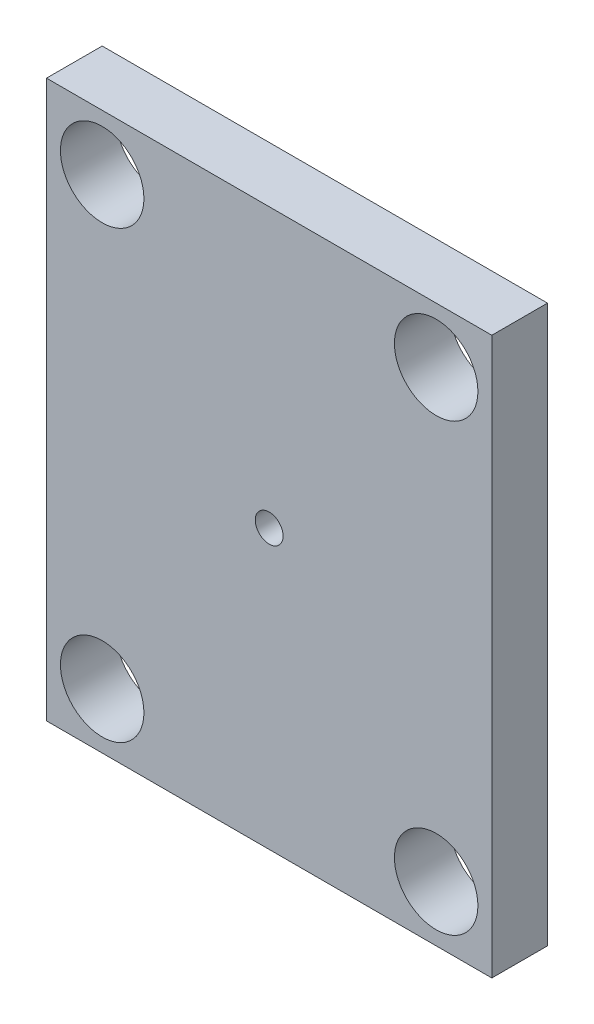
SolidWorks part; units mm, degrees
material "6061 Alloy"
ref_plane "Front" through (0, 0, 0) normal (0, 0, 1) x (1, 0, 0)
ref_plane "Top" through (0, 0, 0) normal (0, 1, 0) x (1, 0, 0)
ref_plane "Right" through (0, 0, 0) normal (1, 0, 0) x (0, 0, -1)
sketch "Sketch1" plane through (0, 0, 0) normal (0, 0, 1) x (1, 0, 0)
  line L1 (0, 0) -> (101.6, 0)
  line L2 (0, 0) -> (0, 127)
  line L3 (0, 127) -> (101.6, 127)
  line L4 (101.6, 0) -> (101.6, 127)
  dimension "D1" = 101.6
  dimension "D2" = 127
extrude "Boss-Extrude1" add sketch "Sketch1" along normal blind 19.05
sketch "Sketch2" plane through (0, 0, 0) normal (0, 0, -1) x (-1, 0, 0)
  line L0 (0, 0) -> (-101.6, 0) construction
  line L1 (-101.6, 127) -> (-76.2, 127)
  line L2 (-101.6, 127) -> (-101.6, 0)
  line L3 (-101.6, 0) -> (-76.2, 0)
  line L4 (-76.2, 127) -> (-76.2, 0)
  line L5 (-50.8, 105.5447) -> (-50.8, -5.5939) construction
  line L6 (-25.4, 127) -> (-25.4, 0)
  line L7 (0, 0) -> (-25.4, 0)
  line L8 (0, 127) -> (0, 0)
  line L9 (0, 127) -> (-25.4, 127)
  dimension "D1" = 25.4
  dimension "D2" = 50.8
extrude "Cut-Extrude1" cut sketch "Sketch2" against normal blind 6.35
sketch "Sketch4" plane through (0, 0, 19.05) normal (0, 0, 1) x (1, 0, 0)
  line L0 (0, 127) -> (0, 0) construction
  line L1 (101.6, 127) -> (0, 127) construction
  line L2 (50.8, 105.5447) -> (50.8, -4.7693) construction
  line L3 (0, 0) -> (101.6, 0) construction
  line L4 (12.7, 114.3) -> (12.7, 127) construction
  line L5 (12.7, 0) -> (12.7, 12.7) construction
  circle A0 centre (12.7, 114.3) radius 6.35
  circle A1 centre (12.7, 12.7) radius 6.35
  circle A2 centre (88.9, 12.7) radius 6.35
  circle A3 centre (88.9, 114.3) radius 6.35
  dimension "D1" = 12.7
  dimension "D2" = 12.7
  dimension "D3" = 12.7
  dimension "D4" = 12.7
extrude "Cut-Extrude2" cut sketch "Sketch4" against normal up to next
sketch "Sketch9" plane through (0, 0, 0) normal (0, 0, -1) x (-1, 0, 0)
  line L0 (-25.4, 127) -> (-25.4, 0) construction
  line L1 (-76.2, 0) -> (-25.4, 0)
  line L2 (-76.2, 0) -> (-76.2, 50.8)
  line L3 (-76.2, 50.8) -> (-25.4, 50.8)
  line L4 (-25.4, 0) -> (-25.4, 50.8)
  line L5 (-25.4, 127) -> (-25.4, 0) construction
  line L6 (-76.2, 127) -> (-25.4, 127)
  line L7 (-76.2, 127) -> (-76.2, 76.2)
  line L8 (-76.2, 76.2) -> (-25.4, 76.2)
  line L9 (-25.4, 127) -> (-25.4, 76.2)
  dimension "D1" = 50.8
  dimension "D2" = 50.8
extrude "Cut-Extrude7" cut sketch "Sketch9" along direction (0, 0, -1) on the side against the normal up to surface (6.35 mm away)
sketch "Sketch11" plane through (0, 0, 19.05) normal (0, 0, 1) x (1, 0, 0)
  line L0 (101.6, 0) -> (101.6, 127) construction
  line L1 (0, 0) -> (101.6, 0) construction
  circle A0 centre (50.8, 63.5) radius 3.175
  dimension "D1" = 6.35
  dimension "D2" = 50.8
  dimension "D3" = 63.5
extrude "Cut-Extrude8" cut sketch "Sketch11" against normal blind 9.525
sketch "Sketch12" plane through (0, 0, 19.05) normal (0, 0, 1) x (1, 0, 0)
  line L0 (101.6, 0) -> (101.6, 127) construction
  line L1 (101.6, 127) -> (0, 127) construction
  line L2 (0, 0) -> (101.6, 0) construction
  circle A0 centre (12.7, 114.3) radius 9.525
  circle A1 centre (88.9, 114.3) radius 9.525
  circle A6 centre (12.7, 12.7) radius 9.525
  circle A7 centre (88.9, 12.7) radius 9.525
  circle A8 centre (88.6325, -89.6755) radius 9.525
  point P15 (0, 0)
  point P16 (0, 0)
  point P17 (0, 0)
  point P18 (0, 0)
  dimension "D1" = 19.05
  dimension "D5" = 19.05
  dimension "D6" = 19.05
  dimension "D7" = 19.05
  dimension "D2" = 12.7
  dimension "D3" = 12.7
  dimension "D4" = 12.7
extrude "Cut-Extrude9" cut sketch "Sketch12" against normal through all
